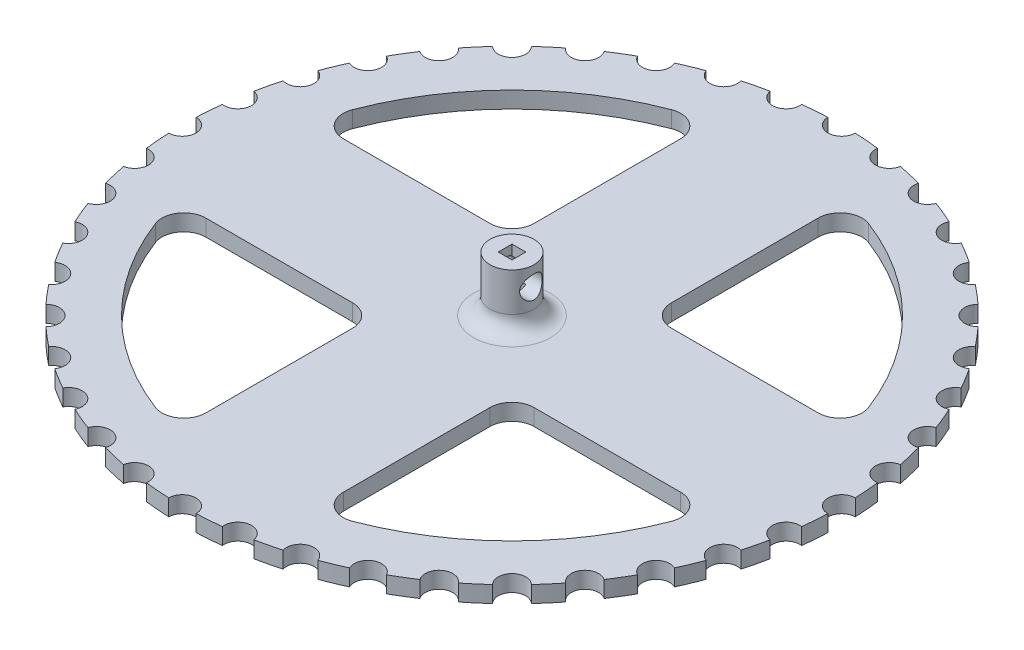
SolidWorks part; units mm, degrees
ref_plane "Front Plane" through (0, 0, 0) normal (0, 0, 1) x (1, 0, 0)
ref_plane "Top Plane" through (0, 0, 0) normal (0, 1, 0) x (1, 0, 0)
ref_plane "Right Plane" through (0, 0, 0) normal (1, 0, 0) x (0, 0, -1)
sketch "Sketch1" plane through (0, 0, 0) normal (0, 1, 0) x (1, 0, 0)
  line L0 (-15.875, 0) -> (-15.875, 61.7981)
  line L1 (-1.5875, -1.5875) -> (1.5875, -1.5875)
  line L2 (-1.5875, -1.5875) -> (-1.5875, 1.5875)
  line L3 (-1.5875, 1.5875) -> (1.5875, 1.5875)
  line L4 (1.5875, -1.5875) -> (1.5875, 1.5875)
  line L5 (-1.5875, -1.5875) -> (1.5875, 1.5875) construction
  line L6 (-1.5875, 1.5875) -> (1.5875, -1.5875) construction
  line L7 (-15.875, 61.7981) -> (-15.875, -61.7981)
  line L8 (0, -15.875) -> (61.7981, -15.875)
  line L9 (61.7981, -15.875) -> (-61.7981, -15.875)
  line L10 (15.875, 0) -> (15.875, 61.7981)
  line L11 (15.875, 61.7981) -> (15.875, -61.7981)
  line L12 (0, 15.875) -> (61.7981, 15.875)
  line L13 (61.7981, 15.875) -> (-61.7981, 15.875)
  circle A0 centre (0, 0) radius 76.2
  circle A1 centre (0, 0) radius 63.8046
  circle A2 centre (0, 0) radius 15.875
  dimension "D1" = 152.4
  dimension "D5" = 31.75
  dimension "D2" = 3.175
  dimension "D3" = 3.175
extrude "Boss-Extrude1" add sketch "Sketch1" along normal blind 3.81 contours L13 A1 L9 L7 L0 | A0 A1 | L7 A1 L11 L8 L9 | L11 A1 L7 L13 L12 | L9 A1 L12 L10 L11 | A2 L13 L0 | A2 L4 L1 L2 L3 | A2 L7 L9 | A2 L8 L11 | A2 L10 L12
fillet "Fillet1" radius 5.08 12 edges at (-61.7981, 1.905, -15.875) (-15.875, 1.905, 61.7981) (-15.875, 1.905, -61.7981) (-15.875, 1.905, -15.875) (15.875, 1.905, -15.875) (61.7981, 1.905, -15.875) (15.875, 1.905, 61.7981) (15.875, 1.905, -61.7981) (-61.7981, 1.905, 15.875) (61.7981, 1.905, 15.875) (15.875, 1.905, 15.875) (-15.875, 1.905, 15.875)
sketch "Sketch2" plane through (0, 3.81, 0) normal (0, 1, 0) x (1, 0, 0)
  line L1 (-1.5875, -1.5875) -> (1.5875, -1.5875)
  line L2 (-1.5875, -1.5875) -> (-1.5875, 1.5875)
  line L3 (-1.5875, 1.5875) -> (1.5875, 1.5875)
  line L4 (1.5875, -1.5875) -> (1.5875, 1.5875)
  line L5 (-1.5875, -1.5875) -> (1.5875, 1.5875) construction
  line L6 (-1.5875, 1.5875) -> (1.5875, -1.5875) construction
  circle A0 centre (0, 0) radius 5.08
  dimension "D1" = 10.16
extrude "Boss-Extrude2" add sketch "Sketch2" along normal blind 12.7
fillet "Fillet2" radius 3.81 1 edges at (0, 3.81, 5.08)
ref_plane "Plane1" through (-5.08, 0, 0) normal (-1, 0, 0) x (0, 0, 1)
sketch "Sketch3" plane through (-5.08, 0, 0) normal (-1, 0, 0) x (0, 0, 1)
  line L0 (0, 16.5302) -> (0, 7.6093) construction
  circle A0 centre (0, 12.0697) radius 2.6
  dimension "D1" = 5.2
extrude "Cut-Extrude1" cut sketch "Sketch3" against normal blind 12.7
sketch "Sketch4" plane through (0, 3.81, 0) normal (0, 1, 0) x (1, 0, 0)
  circle A0 centre (0, 76.2) radius 3.175
  circle A1 centre (0, 0) radius 76.2 construction
  circle A2 centre (11.9203, 75.2619) radius 3.175
  circle A3 centre (23.5471, 72.4705) radius 3.175
  circle A4 centre (34.5941, 67.8947) radius 3.175
  circle A5 centre (44.7892, 61.6471) radius 3.175
  circle A6 centre (53.8815, 53.8815) radius 3.175
  circle A7 centre (61.6471, 44.7892) radius 3.175
  circle A8 centre (67.8947, 34.5941) radius 3.175
  circle A9 centre (72.4705, 23.5471) radius 3.175
  circle A10 centre (75.2619, 11.9203) radius 3.175
  circle A11 centre (76.2, 0) radius 3.175
  circle A12 centre (75.2619, -11.9203) radius 3.175
  circle A13 centre (72.4705, -23.5471) radius 3.175
  circle A14 centre (67.8947, -34.5941) radius 3.175
  circle A15 centre (61.6471, -44.7892) radius 3.175
  circle A16 centre (53.8815, -53.8815) radius 3.175
  circle A17 centre (44.7892, -61.6471) radius 3.175
  circle A18 centre (34.5941, -67.8947) radius 3.175
  circle A19 centre (23.5471, -72.4705) radius 3.175
  circle A20 centre (11.9203, -75.2619) radius 3.175
  circle A21 centre (0, -76.2) radius 3.175
  circle A22 centre (-11.9203, -75.2619) radius 3.175
  circle A23 centre (-23.5471, -72.4705) radius 3.175
  circle A24 centre (-34.5941, -67.8947) radius 3.175
  circle A25 centre (-44.7892, -61.6471) radius 3.175
  circle A26 centre (-53.8815, -53.8815) radius 3.175
  circle A27 centre (-61.6471, -44.7892) radius 3.175
  circle A28 centre (-67.8947, -34.5941) radius 3.175
  circle A29 centre (-72.4705, -23.5471) radius 3.175
  circle A30 centre (-75.2619, -11.9203) radius 3.175
  circle A31 centre (-76.2, 0) radius 3.175
  circle A32 centre (-75.2619, 11.9203) radius 3.175
  circle A33 centre (-72.4705, 23.5471) radius 3.175
  circle A34 centre (-67.8947, 34.5941) radius 3.175
  circle A35 centre (-61.6471, 44.7892) radius 3.175
  circle A36 centre (-53.8815, 53.8815) radius 3.175
  circle A37 centre (-44.7892, 61.6471) radius 3.175
  circle A38 centre (-34.5941, 67.8947) radius 3.175
  circle A39 centre (-23.5471, 72.4705) radius 3.175
  circle A40 centre (-11.9203, 75.2619) radius 3.175
  point P85 (0, 0)
  dimension "D1" = 6.35
  dimension "D2" = 40
extrude "Cut-Extrude2" cut sketch "Sketch4" against normal blind 12.7
